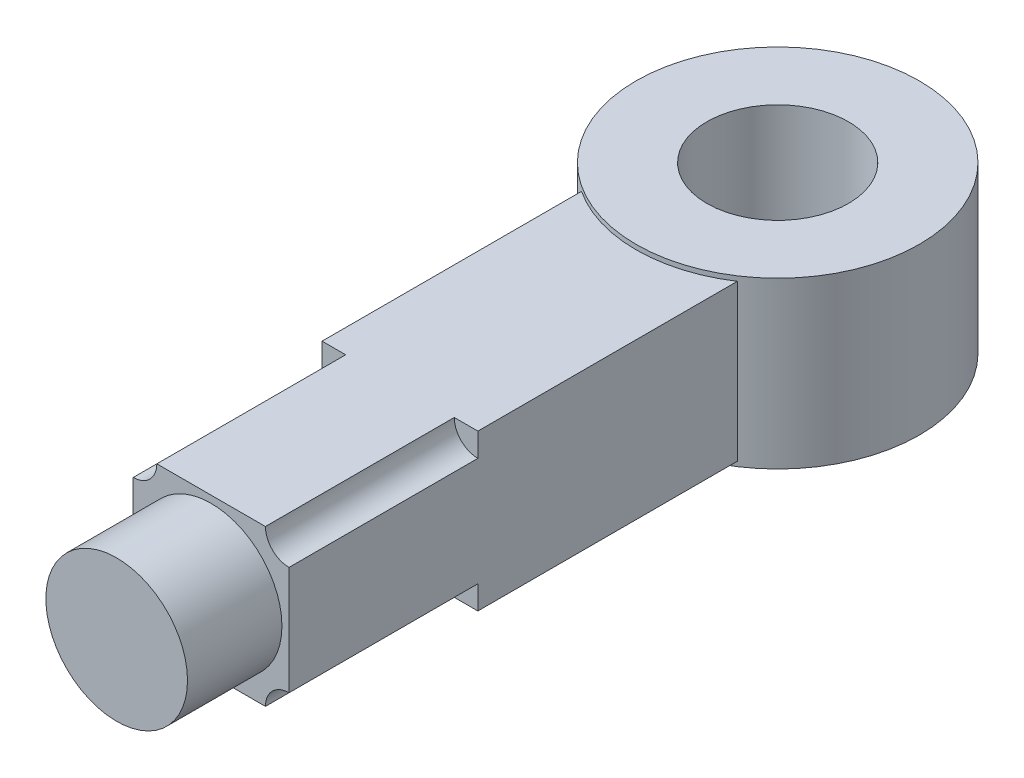
SolidWorks part; units mm, degrees
ref_plane "Front Plane" through (0, 0, 0) normal (0, 0, 1) x (1, 0, 0)
ref_plane "Top Plane" through (0, 0, 0) normal (0, 1, 0) x (1, 0, 0)
ref_plane "Right Plane" through (0, 0, 0) normal (1, 0, 0) x (0, 0, -1)
sketch "Sketch1" plane through (0, 0, 0) normal (0, 1, 0) x (1, 0, 0)
  circle A0 centre (0, 0) radius 30
  dimension "D1" = 60
extrude "Boss-Extrude1" add sketch "Sketch1" along normal mid plane 35
sketch "Sketch2" plane through (0, 0, 0) normal (0, 0, 1) x (1, 0, 0)
  line L1 (-16.5, 16.5) -> (16.5, 16.5)
  line L2 (-16.5, 16.5) -> (-16.5, -16.5)
  line L3 (-16.5, -16.5) -> (16.5, -16.5)
  line L4 (16.5, 16.5) -> (16.5, -16.5)
  line L5 (-16.5, 16.5) -> (16.5, -16.5) construction
  line L6 (-16.5, -16.5) -> (16.5, 16.5) construction
  point P0 (0, 0)
  dimension "D1" = 33
  dimension "D2" = 33
extrude "Boss-Extrude2" add sketch "Sketch2" along normal blind 120
sketch "Sketch3" plane through (0, 0, 120) normal (0, 0, 1) x (1, 0, 0)
  circle A0 centre (0, 0) radius 15
  dimension "D1" = 30
extrude "Boss-Extrude3" add sketch "Sketch3" along normal blind 20
sketch "Sketch4" plane through (0, 0, 120) normal (0, 0, 1) x (1, 0, 0)
  line L0 (16.5, 16.5) -> (-16.5, 16.5) construction
  line L1 (16.5, -16.5) -> (16.5, 16.5) construction
  line L2 (16.5, 11.5) -> (16.5, 16.5)
  line L3 (16.5, 16.5) -> (11.5, 16.5)
  arc A0 (11.5, 16.5) -> (16.5, 11.5) centre (16.5, 16.5) ccw
  dimension "D1" = 5
extrude "Cut-Extrude1" cut sketch "Sketch4" against normal blind 40 and the other way through all
pattern_circular "CirPattern1" count 4 over 360 about axis through (0, 0, 0) along (0, 0, 1) of "Cut-Extrude1"
hole_wizard "Hole1" positions "Sketch5" profile "Sketch6" legacy end condition through all
sketch "Sketch5" plane through (0, 17.5, 0) normal (0, 1, 0) x (1, 0, 0)
  point P0 (0, 0)
sketch "Sketch6" plane through (0, 17.5, 0) normal (1, 0, 0) x (0, 0, 1)
  line L0 (0, 0) -> (0, 35)
  line L1 (0, 35) -> (15, 35)
  line L2 (15, 35) -> (15, 0)
  line L3 (15, 0) -> (0, 0)
  line L4 (0, 110) -> (0, -10) construction
  dimension "Diameter" = 30
  dimension "Depth" = 35
